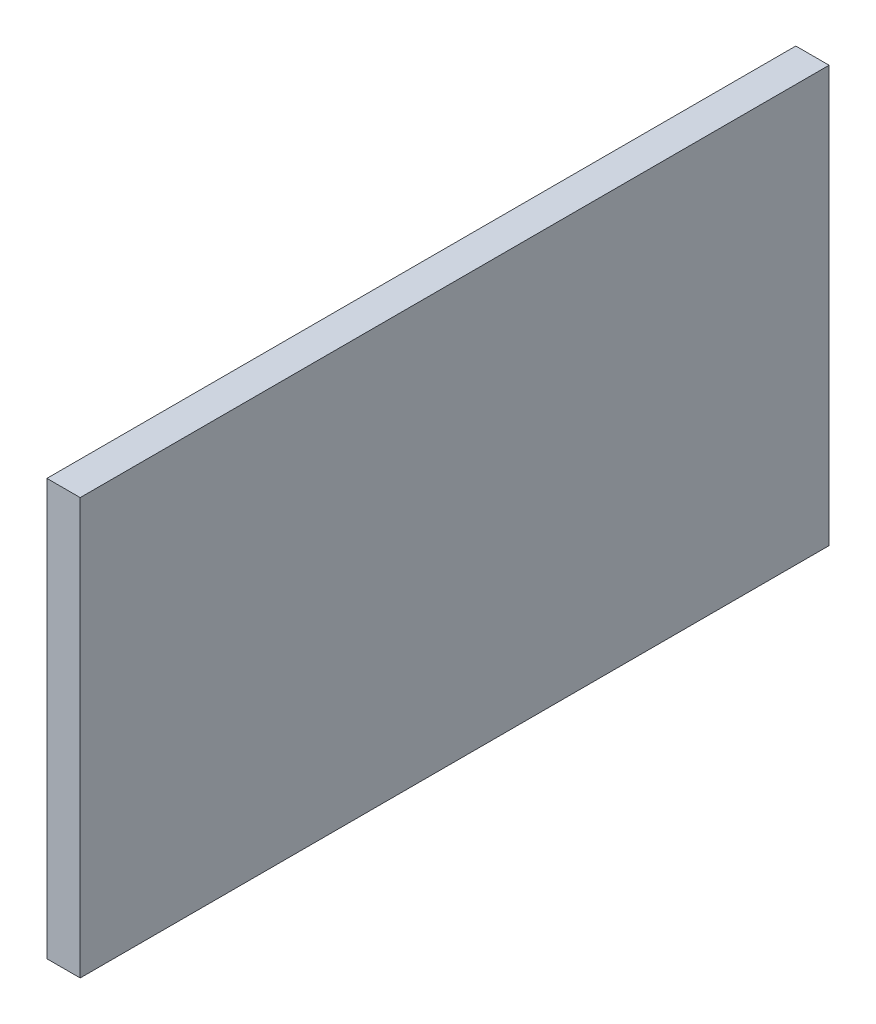
SolidWorks part; units mm, degrees
ref_plane "Front Plane" through (0, 0, 0) normal (0, 0, 1) x (1, 0, 0)
ref_plane "Top Plane" through (0, 0, 0) normal (0, 1, 0) x (1, 0, 0)
ref_plane "Right Plane" through (0, 0, 0) normal (1, 0, 0) x (0, 0, -1)
sketch "Sketch1" plane through (0, 0, 0) normal (1, 0, 0) x (0, 0, -1)
  line L1 (0, 0) -> (90, 0)
  line L2 (0, 0) -> (0, -50)
  line L3 (0, -50) -> (90, -50)
  line L4 (90, 0) -> (90, -50)
  dimension "D1" = 90
  dimension "D2" = 50
extrude "Boss-Extrude1" add sketch "Sketch1" along normal blind 4
